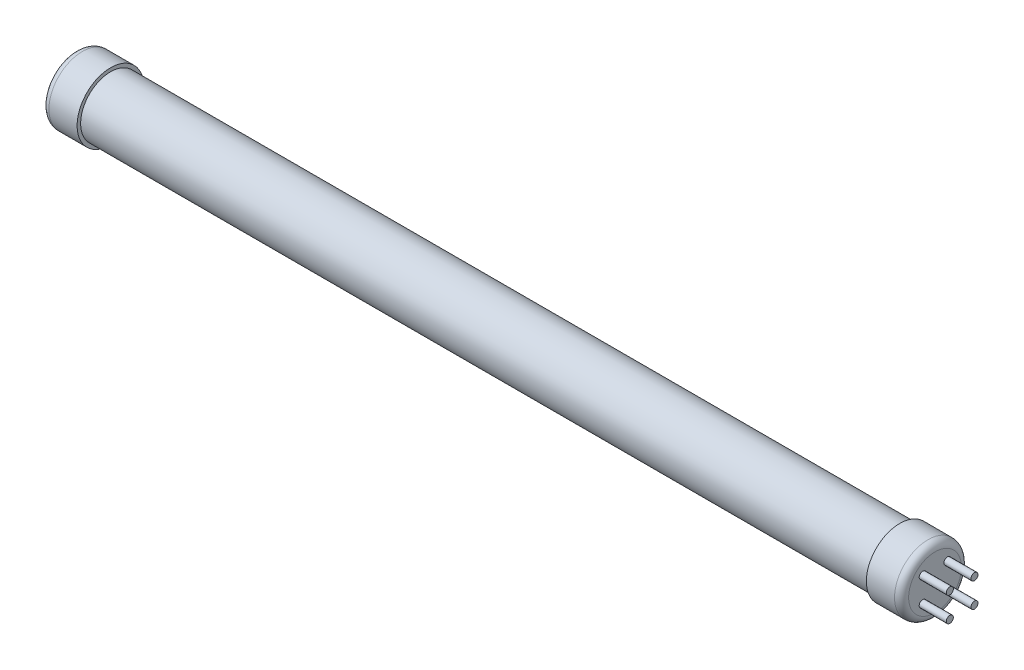
SolidWorks part; units mm, degrees
ref_plane "Front Plane" through (0, 0, 0) normal (0, 0, 1) x (1, 0, 0)
ref_plane "Top Plane" through (0, 0, 0) normal (0, 1, 0) x (1, 0, 0)
ref_plane "Right Plane" through (0, 0, 0) normal (1, 0, 0) x (0, 0, -1)
sketch "Sketch1" plane through (0, 0, 0) normal (0, 1, 0) x (1, 0, 0)
  line L0 (-112.05, 0) -> (112.05, 0) construction
  line L1 (-112.05, 0) -> (-112.05, 8.5)
  line L2 (-112.05, 8.5) -> (112.05, 8.5)
  line L3 (112.05, 8.5) -> (112.05, 0)
  line L4 (112.05, 0) -> (-112.05, 0)
  dimension "D1" = 8.5
  dimension "D2" = 224.1
revolve "Revolve1" add sketch "Sketch1" angle 360 about L0
sketch "Sketch2" plane through (-112.05, 0, 0) normal (-1, 0, 0) x (0, 0, 1)
  circle A0 centre (0, 0) radius 9.5
  circle A1 centre (0, 0) radius 8.5 construction
  dimension "D1" = 1
extrude "Boss-Extrude1" add sketch "Sketch2" along normal blind 10
mirror "Mirror1" about plane through (0, 0, 0) normal (1, 0, 0) of "Boss-Extrude1"
fillet "Fillet1" radius 2 2 edges at (-122.05, 0, 9.5) (122.05, 0, 9.5)
sketch "Sketch3" plane through (122.05, 0, 0) normal (1, 0, 0) x (0, 0, -1)
  line L1 (-3.5, 3.5) -> (3.5, 3.5) construction
  line L2 (-3.5, 3.5) -> (-3.5, -3.5) construction
  line L3 (-3.5, -3.5) -> (3.5, -3.5) construction
  line L4 (3.5, 3.5) -> (3.5, -3.5) construction
  line L5 (-3.5, 3.5) -> (3.5, -3.5) construction
  line L6 (-3.5, -3.5) -> (3.5, 3.5) construction
  circle A0 centre (-3.5, 3.5) radius 1
  circle A1 centre (3.5, 3.5) radius 1
  circle A2 centre (3.5, -3.5) radius 1
  circle A3 centre (-3.5, -3.5) radius 1
  point P0 (0, 0)
  dimension "D1" = 2
  dimension "D2" = 7
extrude "Boss-Extrude2" add sketch "Sketch3" along normal blind 7.7
equation "\"D1@Sketch1\"=(19/2)-1"
